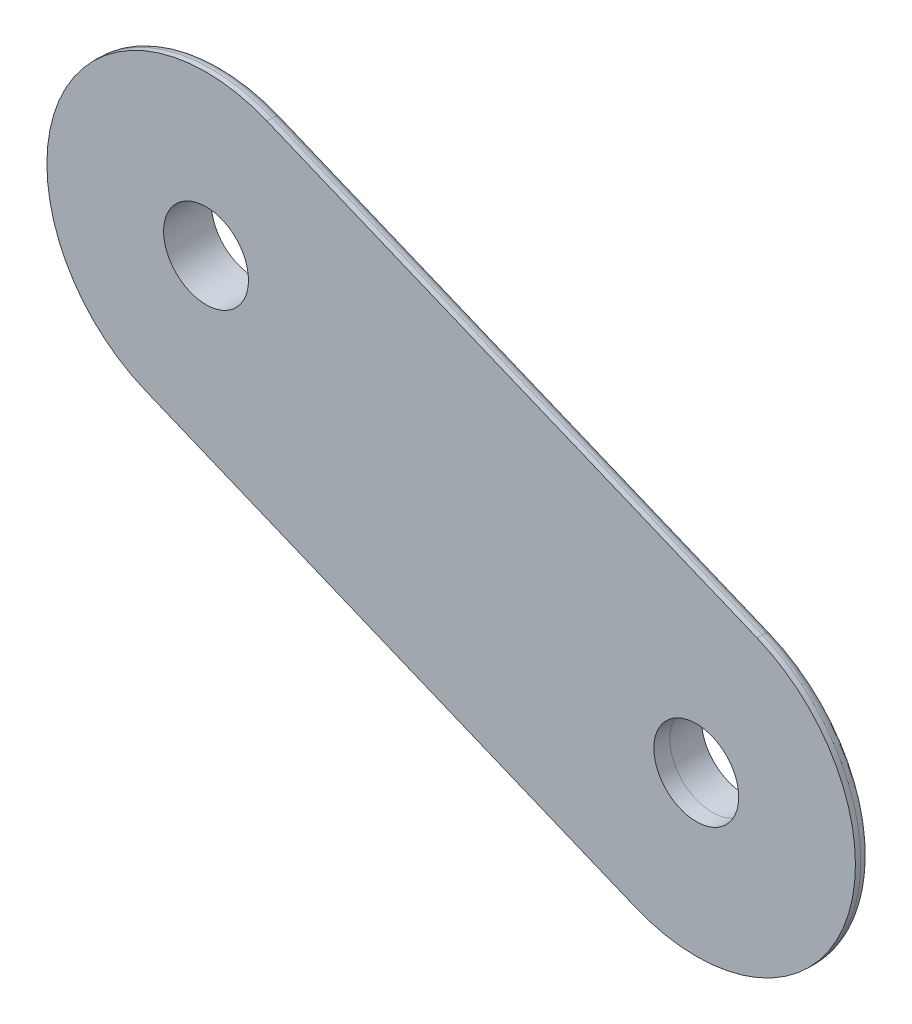
SolidWorks part; units mm, degrees
ref_plane "Front Plane" through (0, 0, 0) normal (0, 0, 1) x (1, 0, 0)
ref_plane "Top Plane" through (0, 0, 0) normal (0, 1, 0) x (1, 0, 0)
ref_plane "Right Plane" through (0, 0, 0) normal (1, 0, 0) x (0, 0, -1)
sketch "Sketch1" plane through (0, 0, 0) normal (0, 0, 1) x (1, 0, 0)
  line L0 (0, 0) -> (46.2112, -19.0925) construction
  line L1 (23.1056, -9.5462) -> (26.6464, -0.9762) construction
  circle A0 centre (0, 0) radius 7.5
  circle A1 centre (0, 0) radius 4
  circle A2 centre (0, 0) radius 4 construction
  circle A3 centre (46.2112, -19.0925) radius 4
  circle A4 centre (46.2112, -19.0925) radius 7.5
  dimension "D1" = 15
extrude "Boss-Extrude1" add sketch "Sketch1" along normal blind 3
sketch "Sketch2" plane through (0, 0, 3) normal (0, 0, 1) x (1, 0, 0)
  line L0 (0, 0) -> (46.2112, -19.0925) construction
  line L1 (23.1056, -9.5462) -> (26.4754, -1.39) construction
  line L2 (5.7277, 13.8634) -> (51.939, -5.2291)
  line L3 (-5.7277, -13.8634) -> (40.4835, -32.9558)
  arc A0 (5.7277, 13.8634) -> (-5.7277, -13.8634) centre (0, 0) ccw
  circle A1 centre (0, 0) radius 4
  circle A2 centre (0, 0) radius 4 construction
  circle A3 centre (46.2112, -19.0925) radius 4
  arc A4 (51.939, -5.2291) -> (40.4835, -32.9558) centre (46.2112, -19.0925) cw
  dimension "D1" = 30
extrude "Boss-Extrude2" add sketch "Sketch2" along normal blind 1.5
fillet "Fillet1" radius 1 4 edges at (-13.8634, 5.7277, 3) (28.8334, 4.3171, 3) (60.0746, -24.8202, 3) (17.3779, -23.4096, 3)
